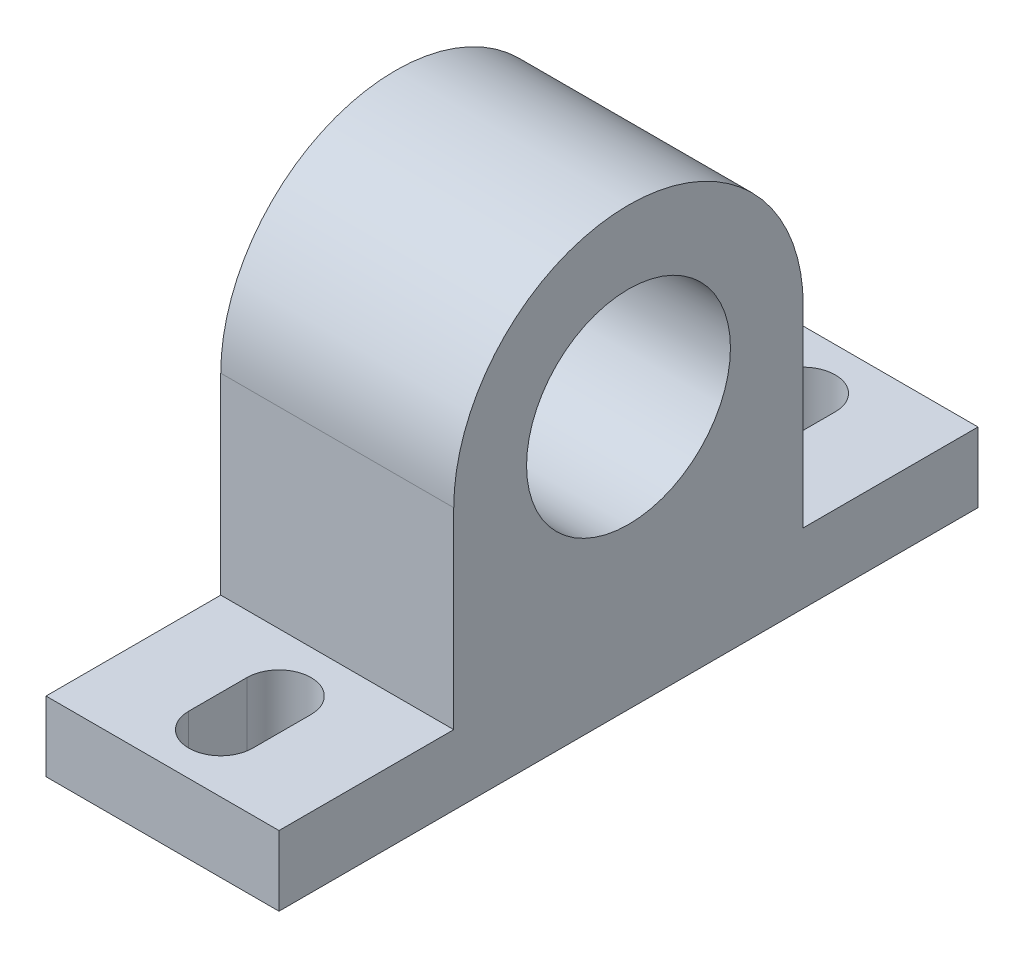
SolidWorks part; units mm, degrees
ref_plane "前视基准面" through (0, 0, 0) normal (0, 0, 1) x (1, 0, 0)
ref_plane "上视基准面" through (0, 0, 0) normal (0, 1, 0) x (1, 0, 0)
ref_plane "右视基准面" through (0, 0, 0) normal (1, 0, 0) x (0, 0, -1)
sketch "草图1" plane through (0, 0, 0) normal (0, 1, 0) x (1, 0, 0)
  line L0 (-20, 60) -> (20, 60)
  line L1 (20, 60) -> (20, -60)
  line L2 (20, -60) -> (-20, -60)
  line L3 (-20, -60) -> (-20, 60)
extrude "凸台-拉伸1" add sketch "草图1" along normal blind 12
ref_plane "基准面1" through (-20, 0, 0) normal (1, 0, 0) x (0, 0, -1)
sketch "草图2" plane through (-20, 0, 0) normal (1, 0, 0) x (0, 0, -1)
  line L0 (30, 10) -> (30, 45)
  line L1 (-30, 45) -> (-30, 10)
  line L2 (-30, 10) -> (30, 10)
  arc A0 (30, 45) -> (-30, 45) centre (0, 45) ccw
extrude "凸台-拉伸2" add sketch "草图2" along normal blind 40
sketch "草图3" plane through (0, 0, 0) normal (1, 0, 0) x (0, 0, -1)
  circle A0 centre (0, 45) radius 17.5
extrude "切除-拉伸1" cut sketch "草图3" against normal mid plane 242
ref_plane "基准面2" through (0, 12, 0) normal (0, 1, 0) x (1, 0, 0)
sketch "草图4" plane through (0, 12, 0) normal (0, 1, 0) x (1, 0, 0)
  line L0 (5.5, -40) -> (5.5, -50)
  line L1 (-5.5, -50) -> (-5.5, -40)
  line L2 (5.5, 50) -> (5.5, 40)
  line L3 (-5.5, 40) -> (-5.5, 50)
  arc A0 (5.5, -50) -> (-5.5, -50) centre (0, -50) cw
  arc A1 (-5.5, -40) -> (5.5, -40) centre (0, -40) cw
  arc A2 (5.5, 40) -> (-5.5, 40) centre (0, 40) cw
  arc A3 (-5.5, 50) -> (5.5, 50) centre (0, 50) cw
extrude "切除-拉伸2" cut sketch "草图4" against normal through all
